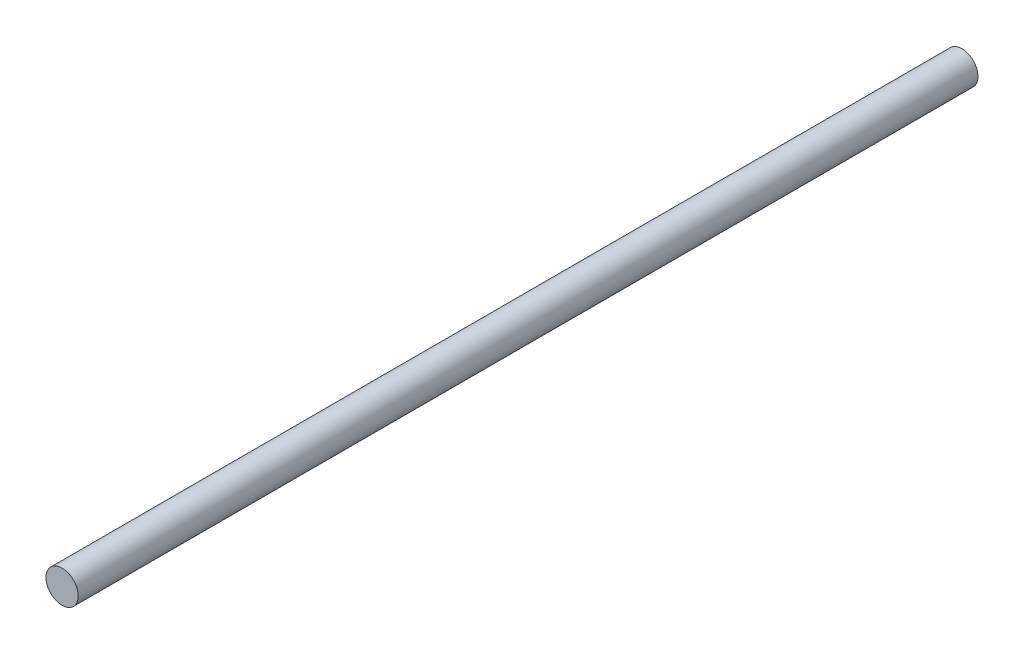
SolidWorks part; units mm, degrees
ref_plane "Front" through (0, 0, 0) normal (0, 0, 1) x (1, 0, 0)
ref_plane "Top" through (0, 0, 0) normal (0, 1, 0) x (1, 0, 0)
ref_plane "Right" through (0, 0, 0) normal (1, 0, 0) x (0, 0, -1)
sketch "Sketch1" plane through (0, 0, 0) normal (0, 0, 1) x (1, 0, 0)
  circle A0 centre (0, 0) radius 4
  dimension "D1" = 8
extrude "Boss-Extrude1" add sketch "Sketch1" along normal blind 223.5
equation "\"D1@Boss-Extrude1\"=223.5mm"
equation "\"D1@Sketch1\"= 8mm"
